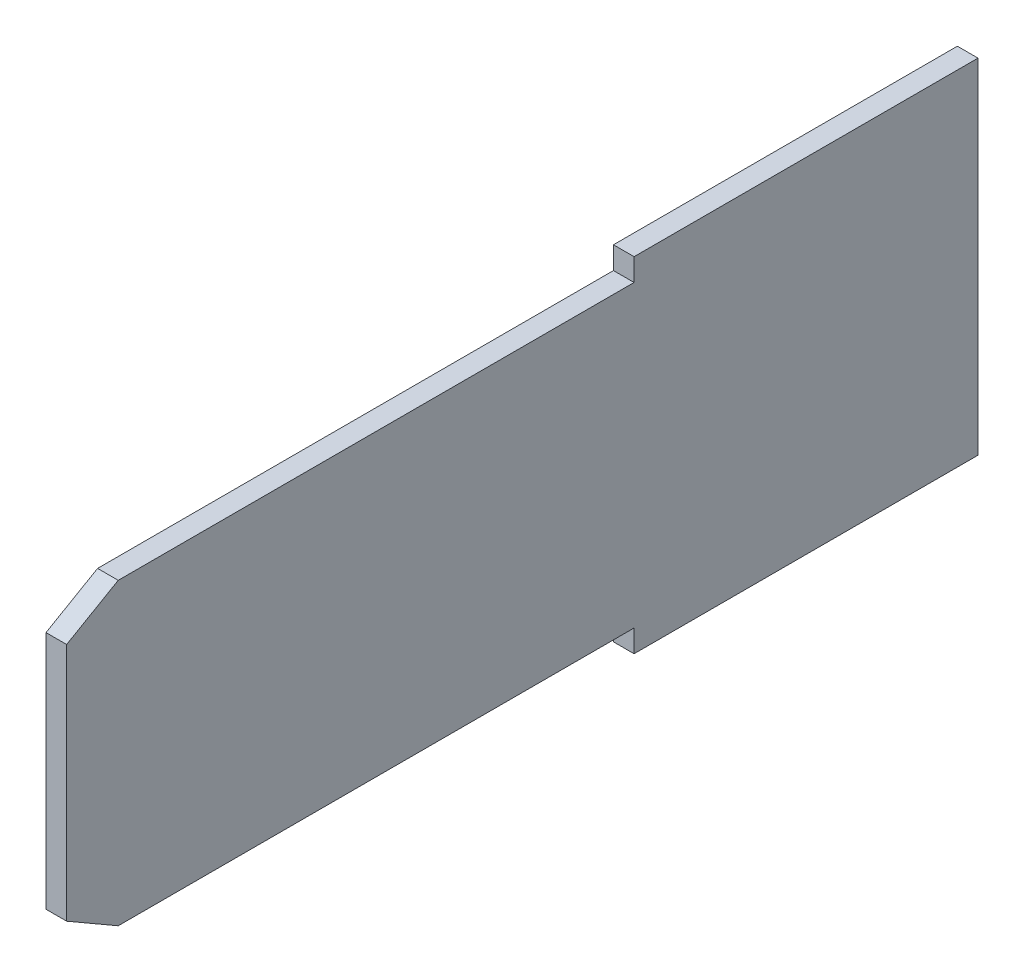
SolidWorks part; units mm, degrees
material "AISI 1020"
ref_plane "Спереди" through (0, 0, 0) normal (0, 0, 1) x (1, 0, 0)
ref_plane "Сверху" through (0, 0, 0) normal (0, 1, 0) x (1, 0, 0)
ref_plane "Справа" through (0, 0, 0) normal (1, 0, 0) x (0, 0, -1)
sketch "Эскиз1" plane through (0, 0, 0) normal (1, 0, 0) x (0, 0, -1)
  line L0 (-1000, 0) -> (49000, 0) construction
  line L1 (100, -50) -> (100, 50)
  line L2 (100, -3) -> (100, 3) construction
  line L3 (100, 50) -> (0, 50)
  line L4 (100, -50) -> (0, -50)
  line L5 (0, 50) -> (0, 43.5)
  line L6 (0, 3) -> (0, 44) construction
  line L7 (0, -50) -> (0, -43.5)
  line L8 (0, 43.5) -> (-150, 43.5)
  line L9 (0, -43.5) -> (-150, -43.5)
  line L10 (-150, 43.5) -> (-165, 34.8397)
  line L11 (-150, -43.5) -> (-165, -34.8397)
  line L12 (-165, 34.8397) -> (-165, -34.8397)
  point P9 (100, 0)
  point P20 (-165, 0)
  dimension "D1" = 6.5
  dimension "D2" = 150
  dimension "D3" = 15
  dimension "D4" = 30
extrude "Бобышка-Вытянуть1" add sketch "Эскиз1" along normal mid plane 6
sketch "Эскиз2" [suppressed] plane through (3, 0, 0) normal (1, 0, 0) x (0, 0, -1)
  line L0 (-165, 34.8397) -> (-165, -34.8397) construction
  line L2 (-165, 3) -> (100, 3)
  line L3 (-165, 3) -> (-165, -50)
  line L4 (-165, -50) -> (100, -50)
  line L5 (100, 3) -> (100, -50)
  dimension "D1" = 3
extrude "Вырез-Вытянуть1" [suppressed] cut sketch "Эскиз2" against normal through all
